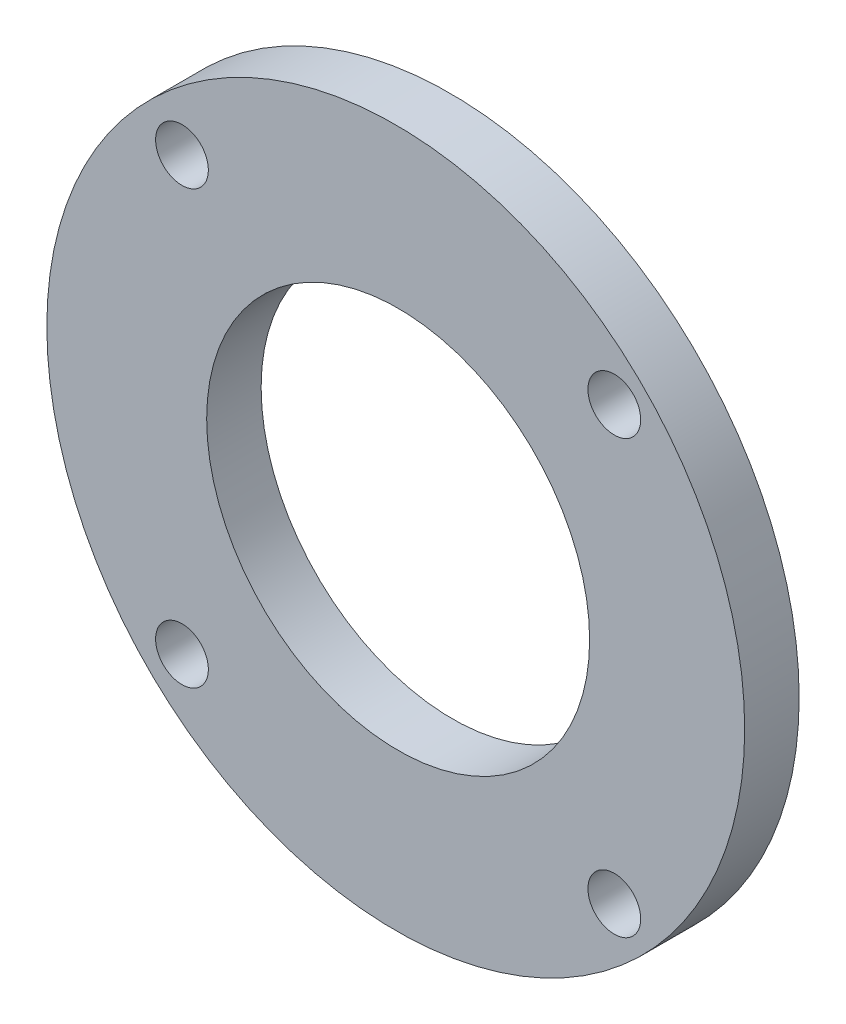
SolidWorks part; units mm, degrees
ref_plane "Front" through (0, 0, 0) normal (0, 0, 1) x (1, 0, 0)
ref_plane "Top" through (0, 0, 0) normal (0, 1, 0) x (1, 0, 0)
ref_plane "Right" through (0, 0, 0) normal (1, 0, 0) x (0, 0, -1)
sketch "Sketch1" plane through (0, 0, 0) normal (0, 0, 1) x (1, 0, 0)
  circle A1 centre (22.0852, 22.2382) radius 20.5
extrude "Extrude1" add sketch "Sketch1" along normal blind 3.2
sketch "Sketch2" plane through (0, 0, 3.2) normal (0, 0, 1) x (1, 0, 0)
  circle A0 centre (22.225, 22.225) radius 11.25
extrude "Cut-Extrude1" cut sketch "Sketch2" against normal through all
sketch "Sketch3" plane through (0, 0, 3.2) normal (0, 0, 1) x (1, 0, 0)
  circle A0 centre (34.925, 34.925) radius 1.55
  circle A1 centre (9.525, 34.925) radius 1.55
  circle A2 centre (34.925, 9.525) radius 1.55
  circle A3 centre (9.525, 9.525) radius 1.55
extrude "Cut-Extrude2" cut sketch "Sketch3" against normal through all
